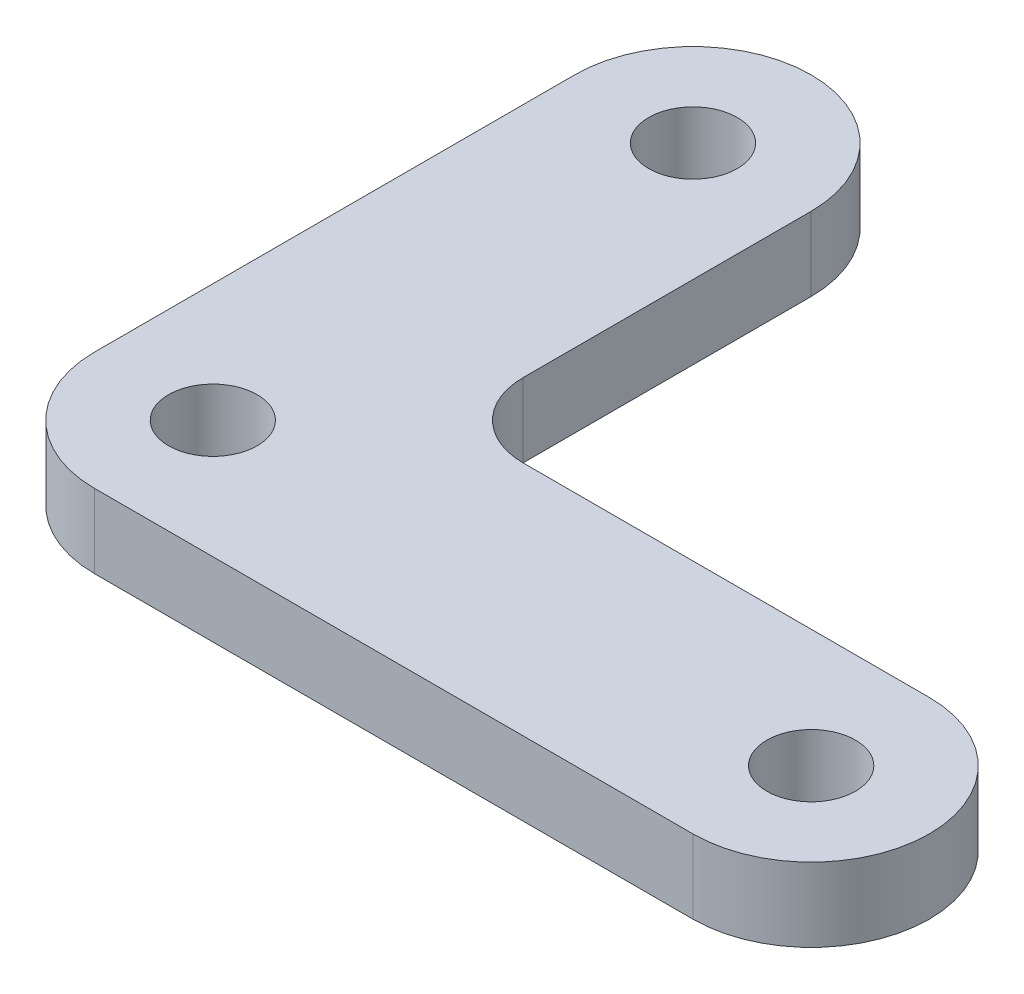
SolidWorks part; units mm, degrees
ref_plane "Front Plane" through (0, 0, 0) normal (0, 0, 1) x (1, 0, 0)
ref_plane "Top Plane" through (0, 0, 0) normal (0, 1, 0) x (1, 0, 0)
ref_plane "Right Plane" through (0, 0, 0) normal (1, 0, 0) x (0, 0, -1)
sketch "Sketch1" plane through (0, 0, 0) normal (0, 1, 0) x (1, 0, 0)
  line L0 (0, 65) -> (0, 0) construction
  line L1 (0, 0) -> (81, 0) construction
  line L2 (-16, 65) -> (-16, 0)
  line L3 (0, -16) -> (81, -16)
  line L4 (81, 16) -> (26, 16)
  line L5 (16, 26) -> (16, 65)
  circle A0 centre (0, 0) radius 6
  circle A1 centre (81, 0) radius 6
  circle A2 centre (0, 65) radius 6
  arc A3 (16, 65) -> (-16, 65) centre (0, 65) ccw
  arc A4 (-16, 0) -> (0, -16) centre (0, 0) ccw
  arc A5 (81, -16) -> (81, 16) centre (81, 0) ccw
  arc A6 (26, 16) -> (16, 26) centre (26, 26) cw
  circle A7 centre (0, 0) radius 16 construction
  circle A8 centre (81, 0) radius 16 construction
  circle A9 centre (0, 65) radius 16 construction
  dimension "D3" = 12
  dimension "D4" = 12
  dimension "D5" = 12
  dimension "D8" = 10
  dimension "D1" = 65
  dimension "D2" = 81
  dimension "D9" = 55
  dimension "D6" = 10
  dimension "D7" = 10
extrude "Boss-Extrude1" add sketch "Sketch1" along normal blind 10
